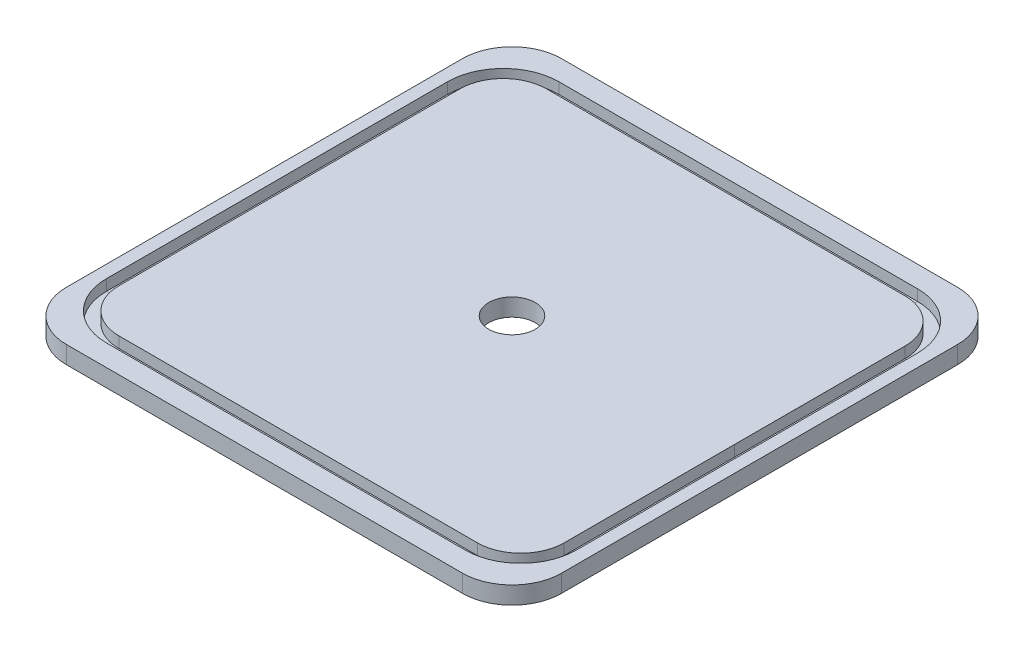
SolidWorks part; units mm, degrees
ref_plane "Front Plane" through (0, 0, 0) normal (0, 0, 1) x (1, 0, 0)
ref_plane "Top Plane" through (0, 0, 0) normal (0, 1, 0) x (1, 0, 0)
ref_plane "Right Plane" through (0, 0, 0) normal (1, 0, 0) x (0, 0, -1)
sketch "Sketch1" plane through (0, 0, 0) normal (0, 1, 0) x (1, 0, 0)
  line L0 (0, 63.5) -> (0, -63.5) construction
  line L12 (-63.5, 50.8) -> (-63.5, -50.8)
  line L13 (-50.8, -63.5) -> (50.8, -63.5)
  line L14 (63.5, -50.8) -> (63.5, 50.8)
  line L15 (50.8, 63.5) -> (-50.8, 63.5)
  arc A0 (50.8, -63.5) -> (63.5, -50.8) centre (50.8, -50.8) ccw
  arc A1 (63.5, 50.8) -> (50.8, 63.5) centre (50.8, 50.8) ccw
  arc A2 (-63.5, -50.8) -> (-50.8, -63.5) centre (-50.8, -50.8) ccw
  arc A3 (-63.5, 50.8) -> (-50.8, 63.5) centre (-50.8, 50.8) cw
  point P11 (-63.5, 0)
  point P15 (0, 63.5)
  point P16 (0, 0)
  dimension "D3" = 12.7
  dimension "D1" = 127
  dimension "D2" = 127
extrude "main body" add sketch "Sketch1" along normal mid plane 4.5
sketch "Sketch29" plane through (0, 2.25, 0) normal (0, 1, 0) x (1, 0, 0)
  line L0 (0, 63.5) -> (0, -63.5)
  line L4 (63.5, -50.8) -> (63.5, 50.8)
  line L5 (50.8, 63.5) -> (-50.8, 63.5)
  line L6 (-63.5, 50.8) -> (-63.5, -50.8)
  line L7 (-50.8, -63.5) -> (50.8, -63.5)
  line L8 (63.5, -50.8) -> (63.5, 50.8)
  line L9 (50.8, 63.5) -> (-50.8, 63.5)
  line L10 (-63.5, 50.8) -> (-63.5, -50.8)
  line L11 (-50.8, -63.5) -> (50.8, -63.5)
  circle A1 centre (0, 0) radius 5.9531
  arc A4 (50.8, -63.5) -> (63.5, -50.8) centre (50.8, -50.8) ccw
  arc A5 (63.5, 50.8) -> (50.8, 63.5) centre (50.8, 50.8) ccw
  arc A6 (-50.8, 63.5) -> (-63.5, 50.8) centre (-50.8, 50.8) ccw
  arc A7 (-63.5, -50.8) -> (-50.8, -63.5) centre (-50.8, -50.8) ccw
  arc A8 (50.8, -63.5) -> (63.5, -50.8) centre (50.8, -50.8) ccw
  arc A9 (63.5, 50.8) -> (50.8, 63.5) centre (50.8, 50.8) ccw
  arc A10 (-50.8, 63.5) -> (-63.5, 50.8) centre (-50.8, 50.8) ccw
  arc A11 (-63.5, -50.8) -> (-50.8, -63.5) centre (-50.8, -50.8) ccw
  dimension "D1" = 0
extrude "PneumaticMount" cut sketch "Sketch29" against normal up to surface (4.5 mm away) up to face at (0, -2.25, 0)
sketch "ORingInsertPath" plane through (0, 2.25, 0) normal (0, 1, 0) x (1, 0, 0)
  line L4 (-45.9922, -56.4388) -> (45.9922, -56.4388)
  line L5 (58.6922, -43.7388) -> (58.6922, 43.7388)
  line L6 (45.9922, 56.4388) -> (-45.9922, 56.4388)
  line L7 (-58.6922, 43.7388) -> (-58.6922, -43.7388)
  line L8 (-45.9922, -56.4388) -> (45.9922, -56.4388)
  line L9 (58.6922, -43.7388) -> (58.6922, 43.7388)
  line L10 (45.9922, 56.4388) -> (-45.9922, 56.4388)
  line L11 (-58.6922, 43.7388) -> (-58.6922, -43.7388)
  line L28 (-58.6922, 0) -> (58.6922, 0) construction
  arc A4 (-58.6922, -43.7388) -> (-45.9922, -56.4388) centre (-45.9922, -43.7388) ccw
  arc A5 (45.9922, -56.4388) -> (58.6922, -43.7388) centre (45.9922, -43.7388) ccw
  arc A6 (58.6922, 43.7388) -> (45.9922, 56.4388) centre (45.9922, 43.7388) ccw
  arc A7 (-45.9922, 56.4388) -> (-58.6922, 43.7388) centre (-45.9922, 43.7388) ccw
  arc A8 (-58.6922, -43.7388) -> (-45.9922, -56.4388) centre (-45.9922, -43.7388) ccw
  arc A9 (45.9922, -56.4388) -> (58.6922, -43.7388) centre (45.9922, -43.7388) ccw
  arc A10 (58.6922, 43.7388) -> (45.9922, 56.4388) centre (45.9922, 43.7388) ccw
  arc A11 (-45.9922, 56.4388) -> (-58.6922, 43.7388) centre (-45.9922, 43.7388) ccw
  dimension "D1" = 0
sketch "ORingInsertProfile" plane through (0, 0, 0) normal (0, 0, 1) x (1, 0, 0)
  line L1 (60.281, 2.25) -> (57.1034, 2.25)
  line L2 (60.281, 2.25) -> (60.281, -0.5745)
  line L3 (60.281, -0.5745) -> (57.1034, -0.5745)
  line L4 (57.1034, 2.25) -> (57.1034, -0.5745)
  line L5 (57.1034, 2.25) -> (60.281, 2.25) construction
  line L6 (5.9531, 2.25) -> (-5.9531, 2.25) construction
  point P8 (58.6922, 2.25)
  dimension "D1" = 3.1775
  dimension "D2" = 2.8245
sweep "O-RingInsert" cut profiles "ORingInsertProfile" path "ORingInsertPath"
equation "\"BodyLength\"= \"BaseLength@BladderAssembly.SLDASM\""
equation "\"BodyWidth\"= \"BaseWidth@BladderAssembly.SLDASM\""
equation "\"HookDepth\"= 0.25"
equation "\"O-RingDiameter\"= 7.512in'McMaster 9396K255"
equation "\"BodyHeight\"= \"overall_thickness\" - \"window_thickness\" - \"sheet_thickness\""
equation "\"window_thickness\"= 0.0625in"
equation "\"sheet_thickness\"= 0.03125in"
equation "\"overall_thickness\"= 7mm"
equation "\"O-RingDiameter\"= 7.512in 'McMaster 9396K255"
equation "\"D2@Sketch1\"=\"BodyLength\""
equation "\"D1@Sketch1\"=\"BodyWidth\""
equation "\"HookWidth\"= 0.25in"
equation "\"D1@ORingInsertProfile\" = 0.9 * \"O-Ring_CS@BladderAssembly.SLDASM\""
equation "\"O-Ring_CutDepth\"= 0.8 * \"O-Ring_CS@BladderAssembly.SLDASM\""
equation "\"D2@ORingInsertProfile\"=\"O-Ring_CutDepth\""
